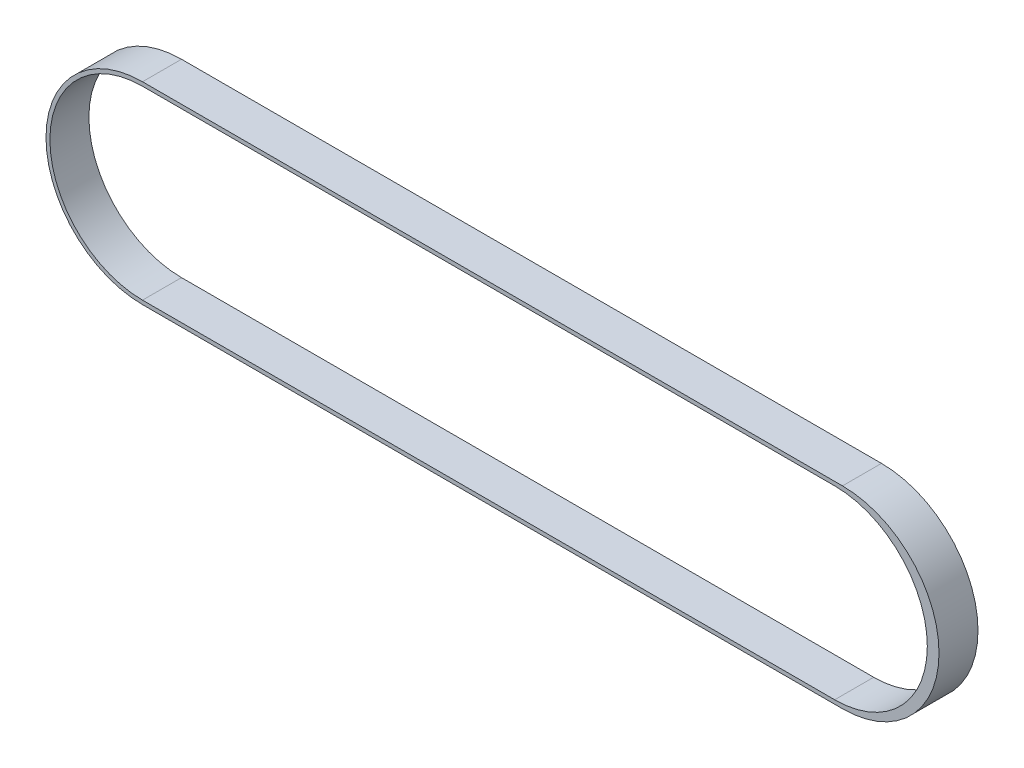
SolidWorks part; units mm, degrees
ref_plane "Front Plane" through (0, 0, 0) normal (0, 0, 1) x (1, 0, 0)
ref_plane "Top Plane" through (0, 0, 0) normal (0, 1, 0) x (1, 0, 0)
ref_plane "Right Plane" through (0, 0, 0) normal (1, 0, 0) x (0, 0, -1)
sketch "Sketch2" plane through (0, 0, 0) normal (0, 0, 1) x (1, 0, 0)
  line L0 (0, 0) -> (227.965, 0) construction
  line L1 (0, 31.4325) -> (227.965, 31.4325)
  line L2 (0, -31.4325) -> (227.965, -31.4325)
  arc A0 (0, 31.4325) -> (0, -31.4325) centre (0, 0) ccw
  arc A1 (227.965, -31.4325) -> (227.965, 31.4325) centre (227.965, 0) ccw
  point P3 (113.9825, 0)
extrude "Boss-Extrude1" add sketch "Sketch2" along normal blind 12.7
sketch "Sketch3" plane through (0, 0, 12.7) normal (0, 0, 1) x (1, 0, 0)
  line L0 (0, 0) -> (225.425, 0) construction
  line L1 (0, 30.1625) -> (225.425, 30.1625)
  line L2 (0, -30.1625) -> (225.425, -30.1625)
  arc A0 (0, 30.1625) -> (0, -30.1625) centre (0, 0) ccw
  arc A1 (225.425, -30.1625) -> (225.425, 30.1625) centre (225.425, 0) ccw
  point P3 (112.7125, 0)
  point P8 (0, 25.5306)
  point P9 (225.1711, 0)
extrude "Cut-Extrude1" cut sketch "Sketch3" against normal blind 12.7
